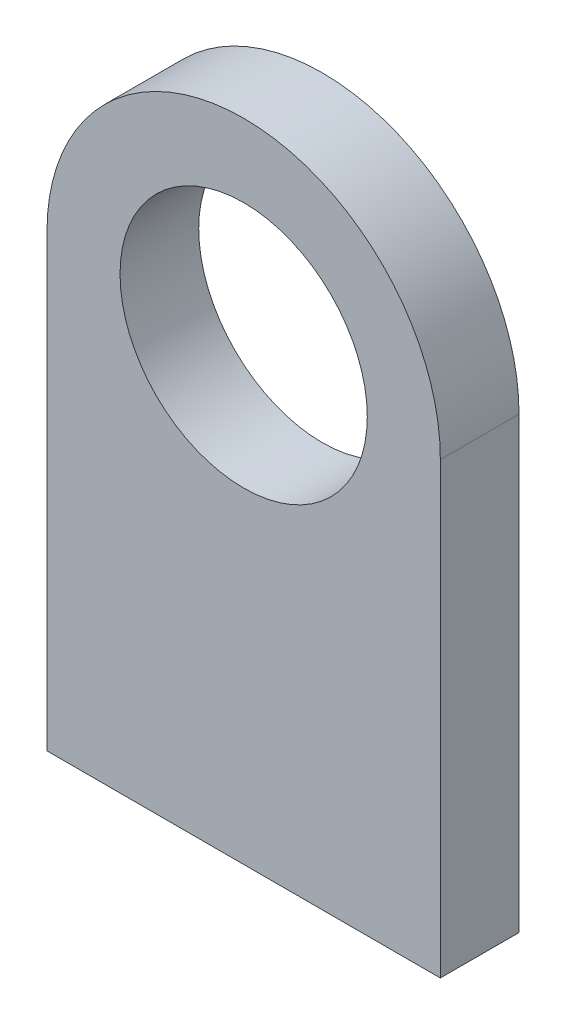
SolidWorks part; units mm, degrees
material "ASTM A36 Aço"
ref_plane "Plano frontal" through (0, 0, 0) normal (0, 0, 1) x (1, 0, 0)
ref_plane "Plano superior" through (0, 0, 0) normal (0, 1, 0) x (1, 0, 0)
ref_plane "Plano direito" through (0, 0, 0) normal (1, 0, 0) x (0, 0, -1)
sketch "Esboço1" plane through (0, 0, 0) normal (0, 0, 1) x (1, 0, 0)
  line L1 (-17.5, -40) -> (17.5, -40)
  line L2 (-17.5, -40) -> (-17.5, 0.0538)
  line L4 (17.5, -40) -> (17.5, -0.0538)
  line L5 (0, 0) -> (0, -40) construction
  line L6 (17.5, -0.0538) -> (17.5, -40)
  arc A0 (17.5, -0.0538) -> (-17.5, 0.0538) centre (0, 0) ccw
  circle A1 centre (0, 0) radius 11
  point P0 (-17.5, 0)
  dimension "D3" = 17.5001
  dimension "D4" = 22
  dimension "D1" = 40
  dimension "D2" = 35
extrude "Ressalto-extrusão1" add sketch "Esboço1" along normal blind 7
